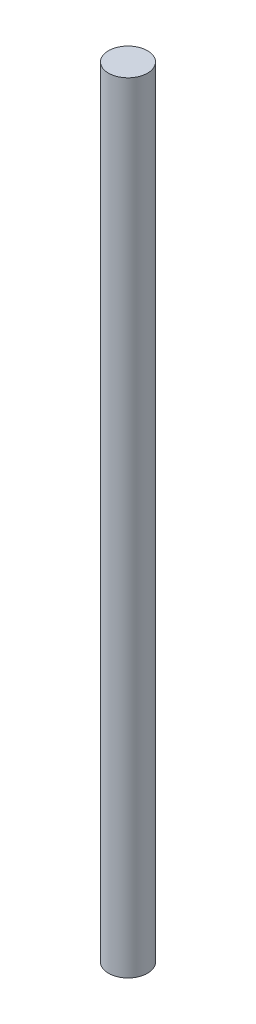
SolidWorks part; units mm, degrees
ref_plane "Front Plane" through (0, 0, 0) normal (0, 0, 1) x (1, 0, 0)
ref_plane "Top Plane" through (0, 0, 0) normal (0, 1, 0) x (1, 0, 0)
ref_plane "Right Plane" through (0, 0, 0) normal (1, 0, 0) x (0, 0, -1)
sketch "Sketch1" plane through (0, 0, 0) normal (0, 1, 0) x (1, 0, 0)
  circle A0 centre (0, 0) radius 12.5
  dimension "D1" = 25
extrude "Boss-Extrude1" add sketch "Sketch1" along normal blind 500
equation "\"D1@Sketch1\" = \"cf_tube_outer_diameter\""
equation "\"D1@Boss-Extrude1\"= \"mid_tube_length\""
equation "\"cf_tube_outer_diameter\" = 25mm"
equation "\"mid_plate_mid_to_top\" = 100mm"
equation "\"mid_plate_mid_to_bottom\" = 125mm"
equation "\"mid_plate_horizontal_spacing\" = 250mm"
equation "\"mid_tube_length\" = 500mm"
